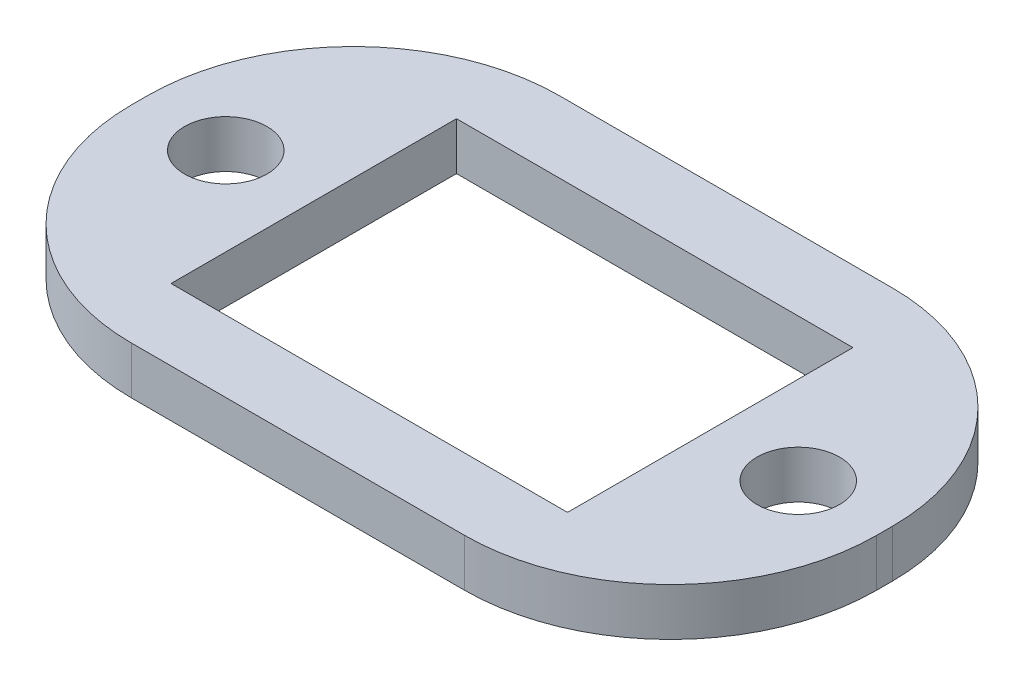
SolidWorks part; units mm, degrees
ref_plane "Front Plane" through (0, 0, 0) normal (0, 0, 1) x (1, 0, 0)
ref_plane "Top Plane" through (0, 0, 0) normal (0, 1, 0) x (1, 0, 0)
ref_plane "Right Plane" through (0, 0, 0) normal (1, 0, 0) x (0, 0, -1)
sketch "Sketch1" plane through (0, 0, 0) normal (0, 1, 0) x (1, 0, 0)
  line L0 (0, 13.5) -> (0, -13.5) construction
  line L1 (-10.5, 13.5) -> (10.5, 13.5)
  line L2 (-23.5, 0.5) -> (-23.5, -0.5)
  line L3 (-10.5, -13.5) -> (10.5, -13.5)
  line L4 (23.5, 0.5) -> (23.5, -0.5)
  line L5 (-23.5, 13.5) -> (23.5, -13.5) construction
  line L6 (-23.5, -13.5) -> (23.5, 13.5) construction
  line L8 (-12.5, 9) -> (12.5, 9)
  line L9 (-12.5, 9) -> (-12.5, -9)
  line L10 (-12.5, -9) -> (12.5, -9)
  line L11 (12.5, 9) -> (12.5, -9)
  line L12 (-12.5, 9) -> (12.5, -9) construction
  line L13 (-12.5, -9) -> (12.5, 9) construction
  circle A0 centre (18.05, 0) radius 2.6
  circle A1 centre (-18.05, 0) radius 2.6
  arc A2 (10.5, 13.5) -> (23.5, 0.5) centre (10.5, 0.5) cw
  arc A3 (10.5, -13.5) -> (23.5, -0.5) centre (10.5, -0.5) ccw
  arc A4 (-23.5, -0.5) -> (-10.5, -13.5) centre (-10.5, -0.5) ccw
  arc A5 (-10.5, 13.5) -> (-23.5, 0.5) centre (-10.5, 0.5) ccw
  point P0 (0, 0)
  point P24 (0, 0)
  dimension "D4" = 5.2
  dimension "D5" = 13
  dimension "D1" = 47
  dimension "D2" = 27
  dimension "D3" = 18.05
  dimension "D6" = 25
  dimension "D7" = 18
extrude "Boss-Extrude1" add sketch "Sketch1" along normal blind 3
